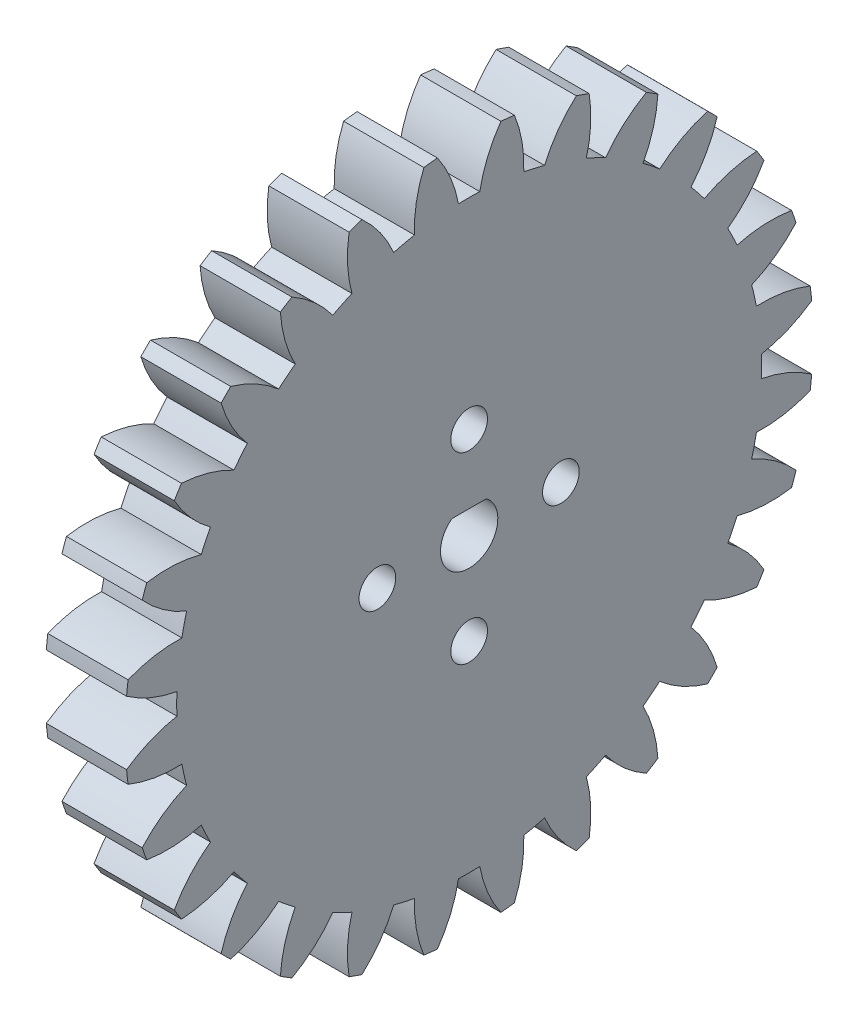
SolidWorks part; units mm, degrees
ref_plane "Plane1" through (0, 0, 0) normal (0, 0, 1) x (1, 0, 0)
ref_plane "Plane2" through (0, 0, 0) normal (0, 1, 0) x (1, 0, 0)
ref_plane "Plane3" through (0, 0, 0) normal (1, 0, 0) x (0, 0, -1)
sketch "HoldingSke" plane through (0, 0, 0) normal (0, 1, 0) x (1, 0, 0)
  line L0 (0, 0) -> (0.4415, -0.2347)
  line L1 (-15, 0) -> (100, 0) construction
  line L2 (0, 0) -> (-2.1039, 2.3779)
  line L3 (0, 0) -> (-11.863, 4.5341)
  line L4 (0, 0) -> (7.6251, 4.0544)
  line L5 (0, 0) -> (-46.8476, -17.4728)
  line L6 (0, 0) -> (-9.9476, -6.7116)
  line L7 (-2.1039, 2.3779) -> (8.6586, 51.2059)
  line L8 (-76.2, 54.61) -> (-76.1, 54.61)
  line L9 (-71.009, 38.7566) -> (-53.1078, 45.2721)
  line L10 (-76.2, 71.12) -> (104.1128, 71.12)
  line L11 (0, 0) -> (-12, 0)
  line L12 (-76.2, 101.6) -> (-76.133, 101.6)
  line L13 (24.9733, 27.94) -> (52.9518, 28.4284)
  line L14 (24.9733, 27.94) -> (24.9743, 27.94)
  line L15 (24.9733, 27.94) -> (100.4006, 29.5858)
  line L16 (-63.627, -2) -> (-12.827, -2)
  circle A0 centre (0, 0) radius 0.1
  circle A1 centre (0, 0) radius 25.499
  circle A2 centre (0, 0) radius 37.5
  circle A3 centre (0, 0) radius 0.1
  dimension "MHD" = 50.998
  dimension "Hub_dia" = 75
  dimension "Bore" = 0.2
  dimension "MBD" = 0.2
  dimension "Num_teeth" = 28
  dimension "Pitch" = 0.5
  dimension "Overall_len" = 50
  dimension "Show_teeth" = 28
  dimension "Thickness" = 12
  dimension "OAL" = 50.0001
  dimension "T_dim" = 0.1
  dimension "Ap" = 20
  dimension "H" = 19.05
  dimension "Pitch_radius" = 180.3128
  dimension "Width" = 12
  dimension "Backlash" = 0.067
  dimension "Addendum_fac" = 1
  dimension "Dedendum_fac" = 1.25
  dimension "Clearance_fac" = 0.25
  dimension "Dedendum_add" = 0.001
  dimension "Module" = 2
sketch "BasProSke" plane through (0, 0, 0) normal (0, 1, 0) x (1, 0, 0)
  line L0 (-10, 0) -> (60, 0) construction
  line L1 (0, 0) -> (0, 30)
  line L2 (0, 0) -> (7, 0)
  line L3 (7, 0) -> (7, 30)
  line L4 (7, 30) -> (0, 30)
  dimension "Thickness" = 7
  dimension "Diameter" = 60
revolve "Base-Revolve" add sketch "BasProSke" angle 360 about L0
sketch "TooCutSke" plane through (0, 0, 0) normal (1, 0, 0) x (0, 0, -1)
  line L1 (0, 0) -> (0, 107) construction
  line L2 (0, 0) -> (-1.6872, 27.9491) construction
  line L3 (0, 0) -> (-6.2616, 55.5729) construction
  line L4 (-1.6872, 27.9491) -> (-3.1308, 27.7865) construction
  arc A0 (0.9285, 25.4821) -> (-0.9285, 25.4821) centre (0, 0) ccw
  arc A1 (2.7859, 29.8959) -> (-2.7859, 29.8959) centre (0, 0) ccw
  circle A2 centre (0, 0) radius 28 construction
  circle A3 centre (0, 0) radius 26.3114 construction
  arc A4 (-0.9285, 25.4821) -> (-2.7859, 29.8959) centre (-11.9418, 23.4453) ccw
  arc A5 (2.7859, 29.8959) -> (0.9285, 25.4821) centre (11.9418, 23.4453) ccw
  dimension "Root_dia" = 50.998
  dimension "Overcut_dia" = 60.0508
  dimension "Pitch_dia" = 56
  dimension "Base_dia" = 52.6228
  dimension "Flank_rad" = 11.2
  dimension "Half_ang" = 6.429
  dimension "Half_CT" = 1.4527
extrude "ToothCut" cut sketch "TooCutSke" along normal through all
fillet "Breaks" [suppressed] radius 0.04
fillet "RootFillets" [suppressed] radius 0.501
pattern_circular "TeethCuts" count 28 every 12.857 about axis through (-10, 0, 0) along (1, 0, 0) of "ToothCut", "RootFillets", "Breaks"
sketch "HubNeaOneSke" plane through (0, 0, 0) normal (-1, 0, 0) x (0, 0, 1)
  circle A0 centre (0, 0) radius 25.499
  dimension "Diameter" = 50.998
extrude "HubNearOne" [suppressed] add sketch "HubNeaOneSke" along normal blind 43.0001
sketch "HubNeaBotSke" plane through (0, 0, 0) normal (-1, 0, 0) x (0, 0, 1)
  circle A0 centre (0, 0) radius 25.499
  dimension "Diameter" = 50.998
extrude "HubNearBoth" [suppressed] add sketch "HubNeaBotSke" along normal blind 21.5
ref_plane "FarPln" through (7, 0, 0) normal (1, 0, 0) x (0, 0, -1)
sketch "HubFarSke" plane through (7, 0, 0) normal (1, 0, 0) x (0, 0, -1)
  circle A0 centre (0, 0) radius 25.499
  dimension "Diameter" = 50.998
extrude "HubFar" [suppressed] add sketch "HubFarSke" along normal blind 21.5
sketch "BorSke" plane through (0, 0, 0) normal (1, 0, 0) x (0, 0, -1)
  circle A0 centre (0, 0) radius 0.1
  dimension "Diameter" = 0.2
extrude "Bore" cut sketch "BorSke" along normal mid plane 100.0001
sketch "KeySke" plane through (0, 0, 0) normal (1, 0, 0) x (0, 0, -1)
  line L0 (-0.05, 0) -> (-0.05, 0.2)
  line L1 (-0.05, 0.2) -> (0.05, 0.2)
  line L2 (0.05, 0.2) -> (0.05, 0)
  line L3 (0, 0) -> (0, 34) construction
  line L4 (-0.05, 0) -> (0.05, 0)
  dimension "Offset" = 0.2
  dimension "Width" = 0.1
extrude "Keyway" [suppressed] cut sketch "KeySke" along normal mid plane 100.0001
pattern_circular "Keyway2" [suppressed] count 2 every 90 about axis through (-10, 0, 0) along (1, 0, 0)
sketch "Schizzo1" plane through (7, 0, 0) normal (1, 0, 0) x (0, 0, -1)
  line L0 (-1.5, 2) -> (1.5, 2)
  arc A0 (-1.5, 2) -> (1.5, 2) centre (0, 0) ccw
  dimension "D1" = 5
  dimension "D2" = 2
extrude "Taglio-Estrusione1" cut sketch "Schizzo1" against normal blind 30
sketch "Schizzo2" plane through (0, 0, 0) normal (-1, 0, 0) x (0, 0, 1)
  circle A0 centre (0, 0) radius 8 construction
  circle A1 centre (0, 8) radius 1.6
  circle A2 centre (8, 0) radius 1.6
  circle A3 centre (0, -8) radius 1.6
  circle A4 centre (-8, 0) radius 1.6
  dimension "D1" = 16
  dimension "D2" = 3.2
extrude "Taglio-Estrusione2" cut sketch "Schizzo2" against normal blind 10
equation "' \"Module@HoldingSke\" = 6.35"
equation "' \"Num_teeth@HoldingSke\" = 12"
equation "' \"Ap@HoldingSke\" =  20"
equation "' \"Ap@HoldingSke\" = 20"
equation "' \"Width@HoldingSke\" = 0.5 * 25.4"
equation "' \"Hub_dia@HoldingSke\"= 1 * 25.4"
equation "' \"Hub_dia@HoldingSke\" = 1 * 25.4"
equation "' \"Overall_len@HoldingSke\" = 1.0 * 25.4"
equation "' \"Bore@HoldingSke\" = 0.75 * 25.4"
equation "' \"T_dim@HoldingSke\" = 0.1 * 25.4"
equation "' \"Width@KeySke\" = 0.25 * 25.4"
equation "' \"Show_teeth@HoldingSke\" = 13"
equation "' \"Backlash@HoldingSke\" = 0.009 * 25.4"
equation "' \"Addendum_fac@HoldingSke\" = 1.0"
equation "' \"Dedendum_fac@HoldingSke\" = 1.25"
equation "' \"Dedendum_add@HoldingSke\" = 0.00005 * 25.4"
equation "' \"Clearance_fac@HoldingSke\" = 0.25"
equation "\"Pitch@HoldingSke\" = 1 / \"Module@HoldingSke\""
equation "\"Overcut_dia@TooCutSke\" = (\"Num_teeth@HoldingSke\" + 2 * \"Addendum_fac@HoldingSke\") / \"Pitch@HoldingSke\" + 0.002 * 25.4"
equation "\"Pitch_dia@TooCutSke\" = \"Num_teeth@HoldingSke\" / \"Pitch@HoldingSke\""
equation "\"Base_dia@TooCutSke\" = \"Num_teeth@HoldingSke\" / \"Pitch@HoldingSke\" * cos((\"Ap@HoldingSke\"  * 3.14159265 / 180))"
equation "\"Root_dia@TooCutSke\" = (\"Num_teeth@HoldingSke\" + 2) / \"Pitch@HoldingSke\" - 2 * (\"Addendum_fac@HoldingSke\" + \"Dedendum_fac@HoldingSke\") / \"Pitch@HoldingSke\" - \"Dedendum_add@HoldingSke\" * 2"
equation "\"Half_ang@TooCutSke\" = 180 / \"Num_teeth@HoldingSke\""
equation "\"Half_CT@TooCutSke\" = \"Num_teeth@HoldingSke\" / \"Pitch@HoldingSke\" * sin((3.14159265 / 2 / \"Num_teeth@HoldingSke\")) / 2 - 7 * \"Backlash@HoldingSke\" / 4"
equation "\"Flank_rad@TooCutSke\" = \"Num_teeth@HoldingSke\" / \"Pitch@HoldingSke\" / 5"
equation "\"Radius@RootFillets\" = \"Clearance_fac@HoldingSke\" / \"Pitch@HoldingSke\" + \"Dedendum_add@HoldingSke\""
equation "\"Break_rad@Breaks\" = 0.02 / \"Pitch@HoldingSke\""
equation "\"Thickness@HoldingSke\" = \"Width@HoldingSke\""
equation "\"OAL@HoldingSke\" = \"Thickness@HoldingSke\""
equation "\"MHD@HoldingSke\" = (\"Num_teeth@HoldingSke\" + 2) / \"Pitch@HoldingSke\" - 2 * (\"Addendum_fac@HoldingSke\" + \"Dedendum_fac@HoldingSke\")  / \"Pitch@HoldingSke\" - \"Dedendum_add@HoldingSke\" * 2"
equation "\"MBD@HoldingSke\" = (\"Num_teeth@HoldingSke\" + 2) / \"Pitch@HoldingSke\" - 2 * (\"Addendum_fac@HoldingSke\" + \"Dedendum_fac@HoldingSke\")  / \"Pitch@HoldingSke\" - \"Dedendum_add@HoldingSke\" * 2 - 0.002 * 25.4"
equation "\"MHD@HoldingSke\" = ((sgn( \"MHD@HoldingSke\" - \"Hub_dia@HoldingSke\" )-1)*( \"MHD@HoldingSke\" - \"Hub_dia@HoldingSke\" ))/-2+ \"Hub_dia@HoldingSke\""
equation "\"MBD@HoldingSke\" = ((sgn( \"MBD@HoldingSke\" - \"Bore@HoldingSke\" )-1)*( \"MBD@HoldingSke\" - \"Bore@HoldingSke\" ))/-2+ \"Bore@HoldingSke\""
equation "\"OAL@HoldingSke\" = ((sgn( \"OAL@HoldingSke\" - \"Overall_len@HoldingSke\" )+1)*( \"OAL@HoldingSke\" - \"Overall_len@HoldingSke\" ))/2 + \"Overall_len@HoldingSke\" + 0.000002 * 25.4"
equation "\"Num_teeth@TeethCuts\" = int( \"Show_teeth@HoldingSke\" ) + 1"
equation "\"Num_teeth@TeethCuts\" = ((sgn( \"Num_teeth@TeethCuts\" - \"Num_teeth@HoldingSke\" )-1)*( \"Num_teeth@TeethCuts\" - \"Num_teeth@HoldingSke\" ))/-2+ \"Num_teeth@HoldingSke\""
equation "\"Num_teeth@TeethCuts\" = ((sgn( \"Num_teeth@TeethCuts\" - 2.0)+1)*( \"Num_teeth@TeethCuts\" - 2.0))/2 +2.0"
equation "\"Angle@TeethCuts\" = 360.0 / \"Num_teeth@HoldingSke\""
equation "\"Diameter@BasProSke\" = (\"Num_teeth@HoldingSke\" + 2 * \"Addendum_fac@HoldingSke\") / \"Pitch@HoldingSke\""
equation "' \"Fillet_rad@BasProSke\" =  \"Thickness@HoldingSke\" * 0.05"
equation "' \"Fillet_rad@BasProSke\" = \"Thickness@HoldingSke\" * 0.05"
equation "\"MHD@HoldingSke\" = ((sgn( \"MHD@HoldingSke\" - \"Root_dia@TooCutSke\" )-1)*( \"MHD@HoldingSke\" - \"Root_dia@TooCutSke\" ))/-2+ \"Root_dia@TooCutSke\""
equation "\"Diameter@HubNeaOneSke\" = \"MHD@HoldingSke\""
equation "\"Length@HubNearOne\" = \"OAL@HoldingSke\" - \"Thickness@BasProSke\""
equation "\"Diameter@HubNeaBotSke\" = \"MHD@HoldingSke\""
equation "\"Length@HubNearBoth\" = ( \"OAL@HoldingSke\" - \"Thickness@BasProSke\" ) / 2.0"
equation "\"Thickness@FarPln\" = \"Thickness@BasProSke\""
equation "\"Diameter@HubFarSke\" = \"MHD@HoldingSke\""
equation "\"Length@HubFar\" = ( \"OAL@HoldingSke\" - \"Thickness@BasProSke\" ) / 2.0"
equation "\"Diameter@BorSke\" = \"MBD@HoldingSke\""
equation "\"D1@Bore\" = \"OAL@HoldingSke\" * 2.0"
equation "\"D1@Keyway\" = \"OAL@HoldingSke\" * 2.0"
equation "\"Offset@KeySke\" = \"T_dim@HoldingSke\" + \"MBD@HoldingSke\" / 2.0"
